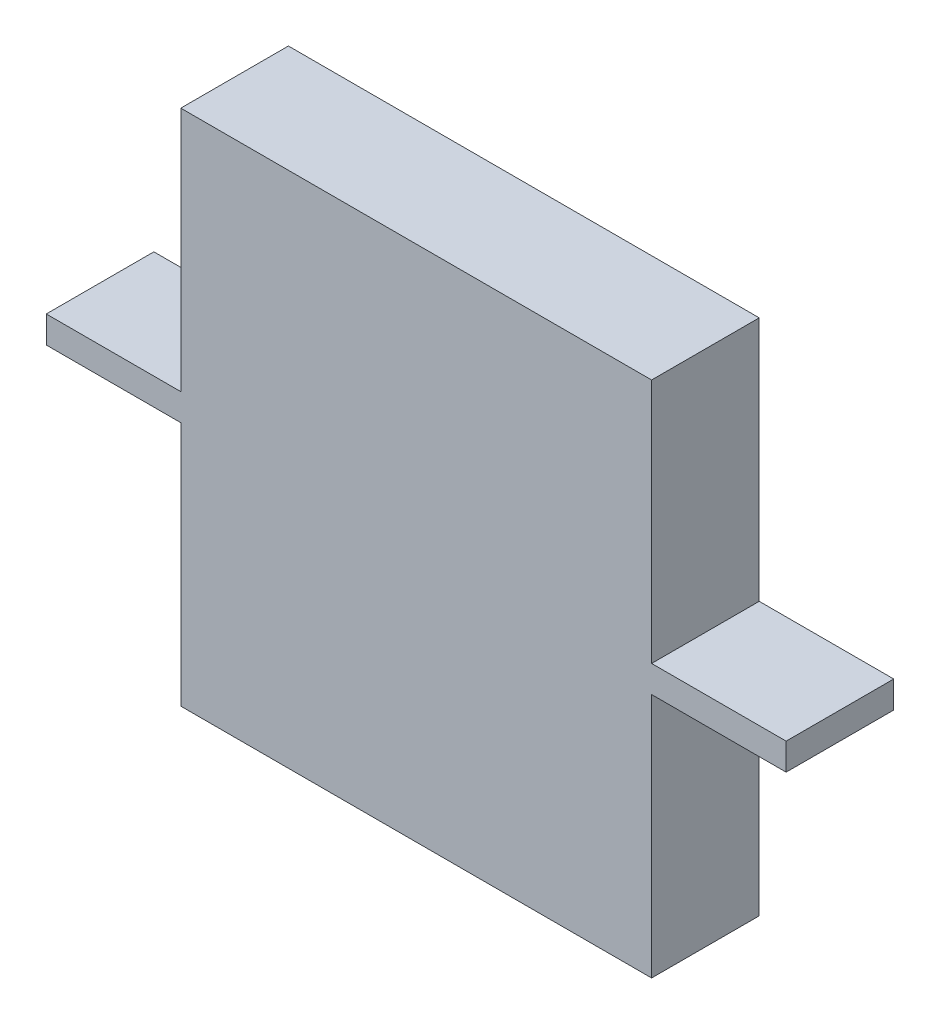
SolidWorks part; units mm, degrees
ref_plane "Front Plane" through (0, 0, 0) normal (0, 0, 1) x (1, 0, 0)
ref_plane "Top Plane" through (0, 0, 0) normal (0, 1, 0) x (1, 0, 0)
ref_plane "Right Plane" through (0, 0, 0) normal (1, 0, 0) x (0, 0, -1)
sketch "Sketch1" plane through (0, 0, 0) normal (0, 0, 1) x (1, 0, 0)
  line L0 (-10, 20.25) -> (0, 38.5) construction
  line L1 (0, 0) -> (35, 0)
  line L2 (0, 0) -> (0, 38.5)
  line L3 (0, 38.5) -> (35, 38.5)
  line L4 (35, 0) -> (35, 38.5)
  line L5 (0, 20.25) -> (-10, 20.25)
  line L6 (0, 20.25) -> (0, 18.25)
  line L7 (0, 18.25) -> (-10, 18.25)
  line L8 (-10, 20.25) -> (-10, 18.25)
  line L9 (-10, 18.25) -> (0, 0) construction
  line L10 (0, 0) -> (0.1904, -0.1403) construction
  line L11 (17.5, 38.5) -> (17.5, 0) construction
  line L12 (45, 20.25) -> (45, 18.25)
  line L13 (35, 18.25) -> (45, 18.25)
  line L14 (35, 20.25) -> (35, 18.25)
  line L15 (35, 20.25) -> (45, 20.25)
  dimension "D1" = 35
  dimension "D2" = 38.5
  dimension "D3" = 2
  dimension "D4" = 10
extrude "Boss-Extrude1" add sketch "Sketch1" along normal blind 8 contours L5 L8 L7 L2 | L1 L4 L3 L2 | L15 L4 L13 L12
